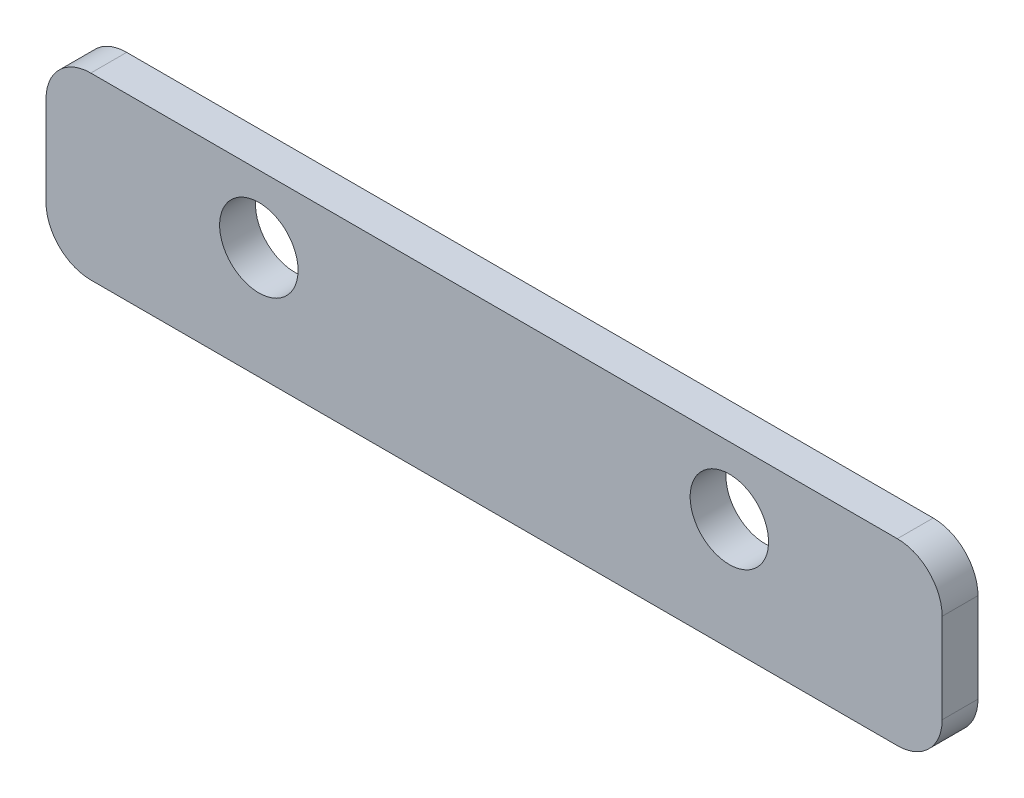
SolidWorks part; units mm, degrees
ref_plane "Спереди" through (0, 0, 0) normal (0, 0, 1) x (1, 0, 0)
ref_plane "Сверху" through (0, 0, 0) normal (0, 1, 0) x (1, 0, 0)
ref_plane "Справа" through (0, 0, 0) normal (1, 0, 0) x (0, 0, -1)
sketch "Эскиз1" plane through (0, 0, 0) normal (0, 0, 1) x (1, 0, 0)
  line L0 (0, 4) -> (0, -4) construction
  line L1 (-18, -4) -> (18, -4)
  line L2 (-20, -2) -> (-20, 2)
  line L3 (-18, 4) -> (18, 4)
  line L4 (20, -2) -> (20, 2)
  line L5 (-20, -4) -> (20, 4) construction
  line L6 (-20, 4) -> (20, -4) construction
  circle A0 centre (-10.5, 1) radius 1.75
  circle A1 centre (10.5, 1) radius 1.75
  arc A2 (18, -4) -> (20, -2) centre (18, -2) ccw
  arc A3 (20, 2) -> (18, 4) centre (18, 2) ccw
  arc A4 (-18, -4) -> (-20, -2) centre (-18, -2) cw
  arc A5 (-20, 2) -> (-18, 4) centre (-18, 2) cw
  point P0 (0, 0)
  dimension "D5" = 3.5
  dimension "D6" = 2
  dimension "D1" = 40
  dimension "D2" = 8
  dimension "D3" = 3
  dimension "D4" = 10.5
extrude "Бобышка-Вытянуть1" add sketch "Эскиз1" along normal blind 1.6 contours A0 | A1 | L3 A3 L4 A2 L1 A4 L2 A5
